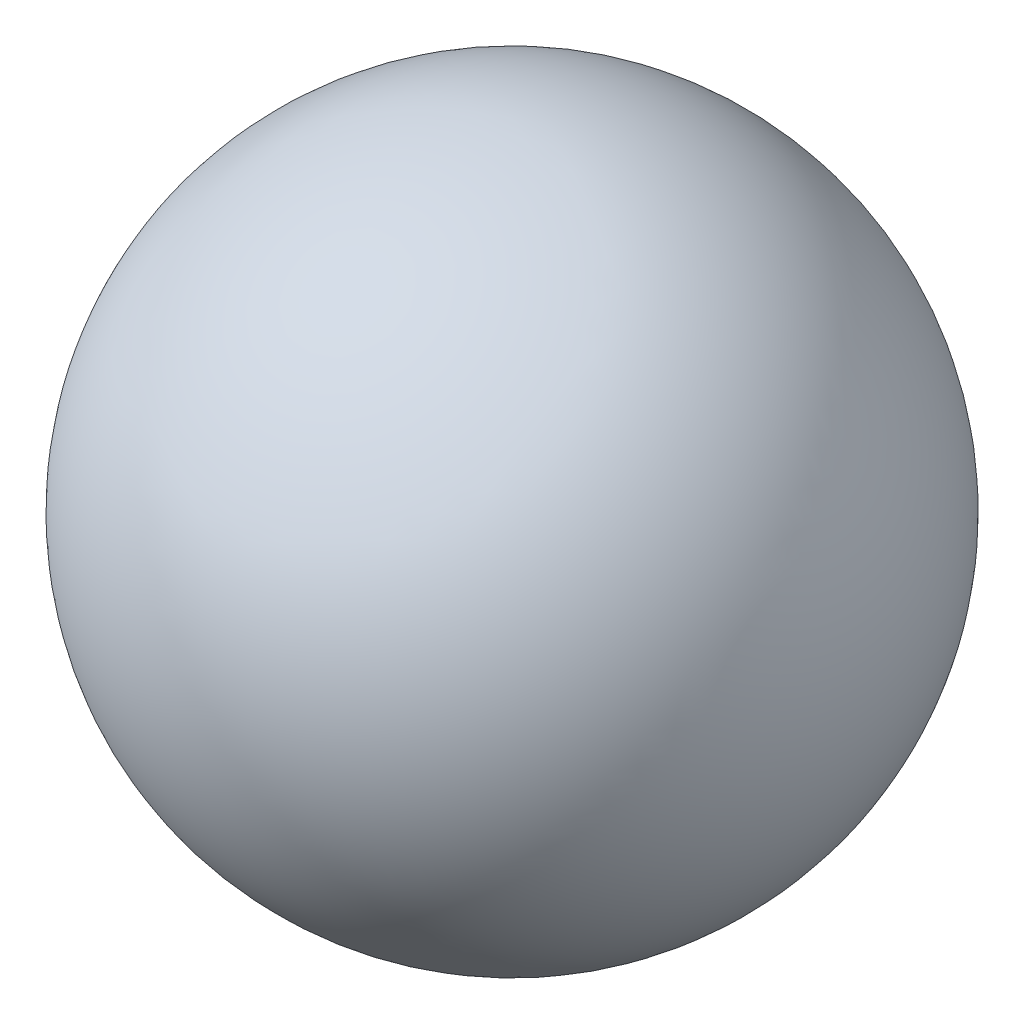
SolidWorks part; units mm, degrees
ref_plane "Plan1" through (0, 0, 0) normal (0, 0, 1) x (1, 0, 0)
ref_plane "Plan2" through (0, 0, 0) normal (0, 1, 0) x (1, 0, 0)
ref_plane "Plan3" through (0, 0, 0) normal (1, 0, 0) x (0, 0, -1)
sketch "Esquisse1" plane through (0, 0, 0) normal (0, 1, 0) x (1, 0, 0)
  line L1 (-0.3, 4.2) -> (9.7, 4.2) construction
  line L2 (-0.3, 8.4) -> (-0.3, 0) construction
  line L3 (9.7, 8.4) -> (9.7, 0) construction
  line L4 (2, 4.2) -> (7.4, 4.2)
  circle A1 centre (4.7, 4.2) radius 2.7 construction
  arc A2 (7.4, 4.2) -> (2, 4.2) centre (4.7, 4.2) ccw
revolve "Base-Révolution" add sketch "Esquisse1" angle 360 about L1
